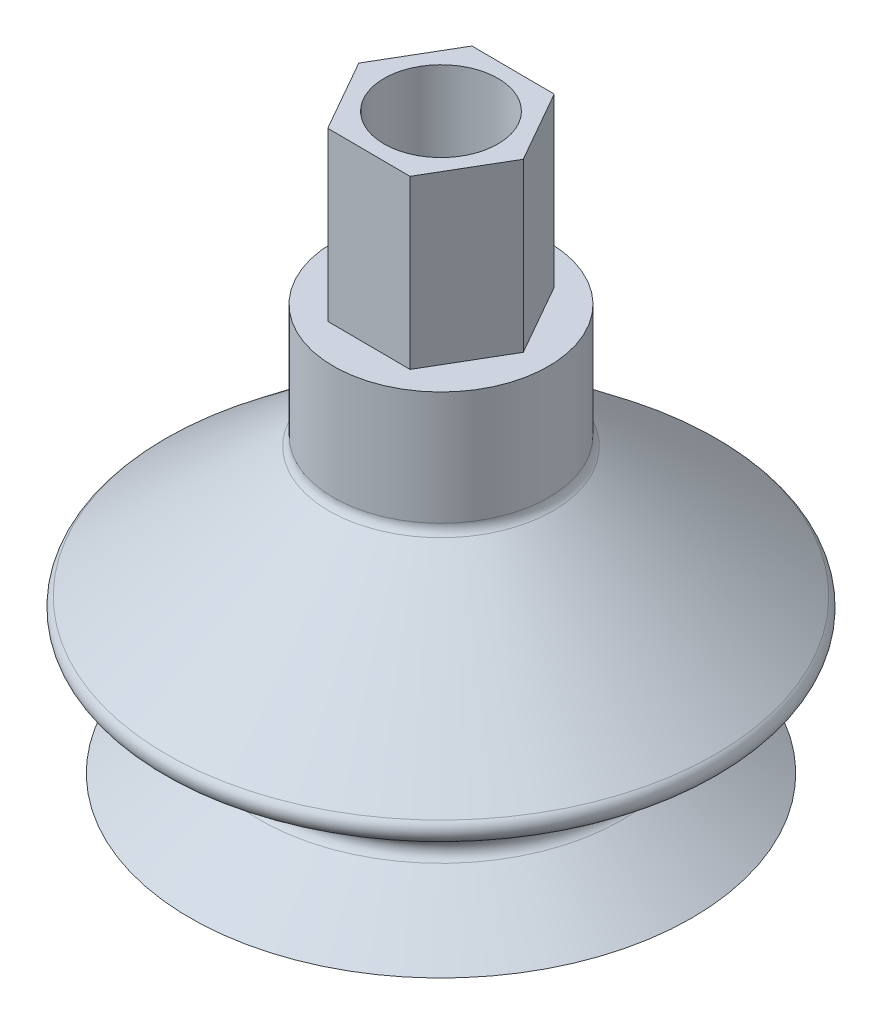
SolidWorks part; units mm, degrees
ref_plane "Front" through (0, 0, 0) normal (0, 0, 1) x (1, 0, 0)
ref_plane "Top" through (0, 0, 0) normal (0, 1, 0) x (1, 0, 0)
ref_plane "Right" through (0, 0, 0) normal (1, 0, 0) x (0, 0, -1)
sketch "Esboço1" plane through (0, 0, 0) normal (0, 0, 1) x (1, 0, 0)
  line L0 (0, 0) -> (21, 0)
  line L1 (21, 0) -> (14, 5)
  line L2 (14, 5) -> (24, 12)
  line L3 (24, 12) -> (9, 24)
  line L4 (9, 24) -> (9, 34)
  line L5 (9, 34) -> (0, 34)
  line L6 (0, 34) -> (0, 0)
  dimension "D1" = 10
  dimension "D2" = 34
  dimension "D3" = 21
  dimension "D4" = 24
  dimension "D5" = 14
  dimension "D6" = 9
  dimension "D7" = 5
  dimension "D8" = 7
revolve "Revolução1" add sketch "Esboço1" angle 360 about L6
shell "Casca1" thickness 0.9
fillet "Filete1" radius 1 3 edges at (-24, 12, 0) (-14, 5, 0) (-9, 24, 0)
sketch "Esboço2" plane through (0, 34, 0) normal (0, 1, 0) x (1, 0, 0)
  line L1 (3.5, 5.9791) -> (-3.4281, 6.0206)
  line L2 (-3.4281, 6.0206) -> (-6.9281, 0.0415)
  line L3 (-6.9281, 0.0415) -> (-3.5, -5.9791)
  line L4 (-3.5, -5.9791) -> (3.4281, -6.0206)
  line L5 (3.4281, -6.0206) -> (6.9281, -0.0415)
  line L6 (6.9281, -0.0415) -> (3.5, 5.9791)
  circle A0 centre (0, 0) radius 6 construction
  dimension "D1" = 12
extrude "Ressalto-extrusão1" add sketch "Esboço2" along normal blind 14
sketch "Esboço3" plane through (0, 48, 0) normal (0, 1, 0) x (1, 0, 0)
  circle A0 centre (0, 0) radius 4.7625
  dimension "D1" = 9.525
extrude "Corte-extrusão1" cut sketch "Esboço3" against normal through all
ref_plane "Plano1" through (0, -4.54, 0) normal (0, -1, 0) x (-1, 0, 0)
sketch "Croquis1" plane through (0, -4.54, 0) normal (0, -1, 0) x (-1, 0, 0)
  circle A0 centre (0, 0) radius 20
